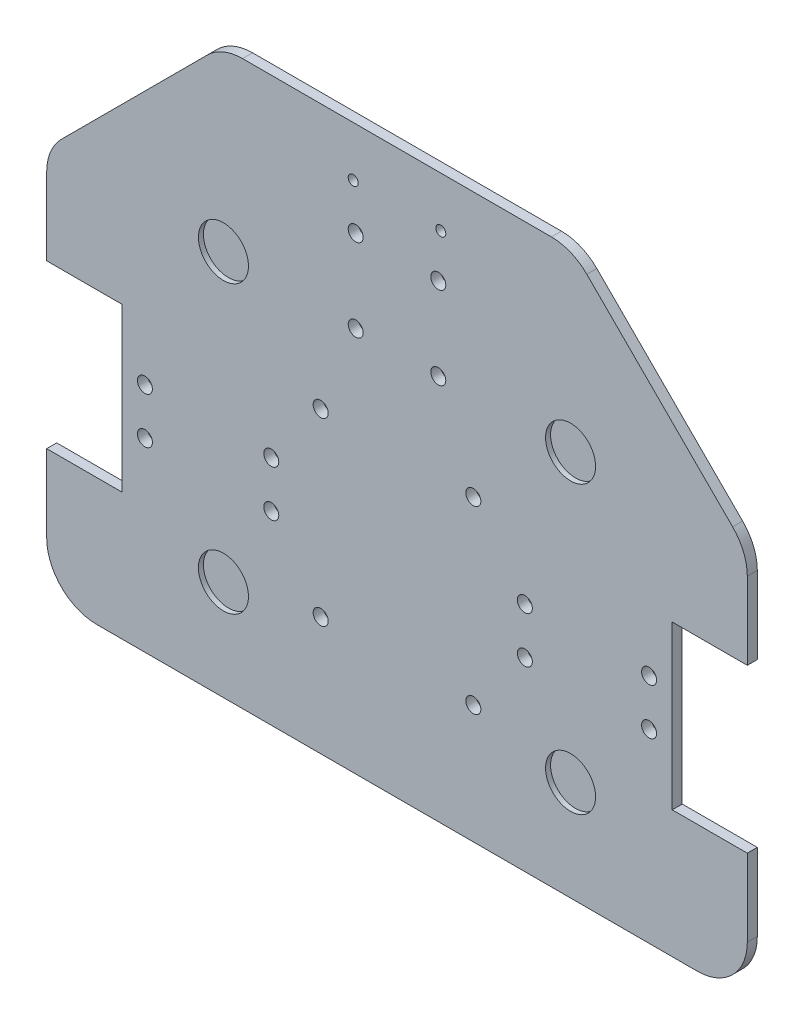
SolidWorks part; units mm, degrees
ref_plane "前视基准面" through (0, 0, 0) normal (0, 0, 1) x (1, 0, 0)
ref_plane "上视基准面" through (0, 0, 0) normal (0, 1, 0) x (1, 0, 0)
ref_plane "右视基准面" through (0, 0, 0) normal (1, 0, 0) x (0, 0, -1)
sketch "草图3" plane through (0, 0, 0) normal (0, 0, 1) x (1, 0, 0)
  line L1 (73.5057, 259.0895) -> (196.9372, 259.0895)
  line L2 (-4.7785, 180.8052) -> (-4.7785, 54.0895)
  line L3 (15.2215, 34.0895) -> (255.2215, 34.0895)
  line L4 (275.2215, 180.8052) -> (275.2215, 54.0895)
  line L6 (1.0793, 194.9474) -> (59.3636, 253.2316)
  line L9 (211.0793, 253.2316) -> (269.3636, 194.9474)
  arc A0 (73.5057, 259.0895) -> (59.3636, 253.2316) centre (73.5057, 239.0895) ccw
  arc A1 (211.0793, 253.2316) -> (196.9372, 259.0895) centre (196.9372, 239.0895) ccw
  arc A2 (1.0793, 194.9474) -> (-4.7785, 180.8052) centre (15.2215, 180.8052) ccw
  arc A3 (-4.7785, 54.0895) -> (15.2215, 34.0895) centre (15.2215, 54.0895) ccw
  arc A4 (255.2215, 34.0895) -> (275.2215, 54.0895) centre (255.2215, 54.0895) ccw
  arc A5 (275.2215, 180.8052) -> (269.3636, 194.9474) centre (255.2215, 180.8052) ccw
  dimension "D1" = 20
  dimension "D2" = 20
  dimension "D3" = 20
extrude "凸台-拉伸1" add sketch "草图3" along normal blind 4
sketch "电池槽" plane through (0, 0, 0) normal (0, 0, 1) x (1, 0, 0)
  line L0 (135.2215, 259.0895) -> (135.2215, 34.0895) construction
  line L1 (-4.7785, 117.4474) -> (275.2215, 117.4474) construction
  line L2 (99.7215, 158.4474) -> (99.7215, 76.4474)
  line L3 (99.7215, 76.4474) -> (170.7215, 76.4474)
  line L4 (170.7215, 158.4474) -> (170.7215, 76.4474)
  line L5 (107.7215, 150.4474) -> (162.7215, 150.4474)
  line L6 (59.3636, 253.2316) -> (1.0793, 194.9474)
  line L7 (-4.7785, 180.8052) -> (-4.7785, 54.0895)
  line L8 (15.2215, 34.0895) -> (255.2215, 34.0895)
  line L9 (275.2215, 54.0895) -> (275.2215, 180.8052)
  line L10 (269.3636, 194.9474) -> (211.0793, 253.2316)
  line L11 (196.9372, 259.0895) -> (73.5057, 259.0895)
  line L12 (59.3636, 253.2316) -> (1.0793, 194.9474)
  line L13 (-4.7785, 180.8052) -> (-4.7785, 54.0895)
  line L14 (15.2215, 34.0895) -> (255.2215, 34.0895)
  line L15 (275.2215, 54.0895) -> (275.2215, 180.8052)
  line L16 (269.3636, 194.9474) -> (211.0793, 253.2316)
  line L17 (196.9372, 259.0895) -> (73.5057, 259.0895)
  line L18 (107.7215, 150.4474) -> (107.7215, 84.4474)
  line L19 (107.7215, 84.4474) -> (162.7215, 84.4474)
  line L20 (162.7215, 150.4474) -> (162.7215, 84.4474)
  line L21 (107.7215, 150.4474) -> (162.7215, 84.4474) construction
  line L22 (107.7215, 84.4474) -> (162.7215, 150.4474) construction
  line L23 (99.7215, 158.4474) -> (170.7215, 158.4474)
  line L24 (99.7215, 158.4474) -> (107.7215, 150.4474) construction
  line L25 (107.7215, 84.4474) -> (99.7215, 76.4474) construction
  line L26 (162.7215, 84.4474) -> (170.7215, 76.4474) construction
  line L27 (162.7215, 150.4474) -> (170.7215, 158.4474) construction
  circle A4 centre (104.7215, 153.4474) radius 3
  circle A5 centre (104.7215, 81.4474) radius 3
  arc A6 (73.5057, 259.0895) -> (59.3636, 253.2316) centre (73.5057, 239.0895) ccw
  arc A7 (1.0793, 194.9474) -> (-4.7785, 180.8052) centre (15.2215, 180.8052) ccw
  arc A8 (-4.7785, 54.0895) -> (15.2215, 34.0895) centre (15.2215, 54.0895) ccw
  arc A9 (255.2215, 34.0895) -> (275.2215, 54.0895) centre (255.2215, 54.0895) ccw
  arc A10 (275.2215, 180.8052) -> (269.3636, 194.9474) centre (255.2215, 180.8052) ccw
  arc A11 (211.0793, 253.2316) -> (196.9372, 259.0895) centre (196.9372, 239.0895) ccw
  arc A12 (73.5057, 259.0895) -> (59.3636, 253.2316) centre (73.5057, 239.0895) ccw
  arc A13 (1.0793, 194.9474) -> (-4.7785, 180.8052) centre (15.2215, 180.8052) ccw
  arc A14 (-4.7785, 54.0895) -> (15.2215, 34.0895) centre (15.2215, 54.0895) ccw
  arc A15 (255.2215, 34.0895) -> (275.2215, 54.0895) centre (255.2215, 54.0895) ccw
  arc A16 (275.2215, 180.8052) -> (269.3636, 194.9474) centre (255.2215, 180.8052) ccw
  arc A17 (211.0793, 253.2316) -> (196.9372, 259.0895) centre (196.9372, 239.0895) ccw
  circle A18 centre (165.7215, 81.4474) radius 3
  circle A19 centre (165.7215, 153.4474) radius 3
  point P31 (135.2215, 117.4474)
  dimension "D2" = 8
  dimension "D1" = 0
sketch "轮槽" plane through (0, 0, 4) normal (0, 0, 1) x (1, 0, 0)
  line L4 (245.2215, 84.9474) -> (275.2215, 84.9474)
  line L5 (-4.7785, 149.9474) -> (7.2215, 149.9474)
  line L6 (59.3636, 253.2316) -> (1.0793, 194.9474)
  line L7 (-4.7785, 180.8052) -> (-4.7785, 54.0895)
  line L8 (15.2215, 34.0895) -> (255.2215, 34.0895)
  line L9 (275.2215, 54.0895) -> (275.2215, 180.8052)
  line L10 (269.3636, 194.9474) -> (211.0793, 253.2316)
  line L11 (196.9372, 259.0895) -> (73.5057, 259.0895)
  line L12 (59.3636, 253.2316) -> (1.0793, 194.9474)
  line L13 (-4.7785, 180.8052) -> (-4.7785, 54.0895)
  line L14 (15.2215, 34.0895) -> (255.2215, 34.0895)
  line L15 (275.2215, 54.0895) -> (275.2215, 180.8052)
  line L16 (269.3636, 194.9474) -> (211.0793, 253.2316)
  line L17 (196.9372, 259.0895) -> (73.5057, 259.0895)
  line L18 (7.2215, 149.9474) -> (25.2215, 149.9474)
  line L19 (25.2215, 149.9474) -> (25.2215, 84.9474)
  line L20 (25.2215, 84.9474) -> (-4.7785, 84.9474)
  line L21 (245.2215, 149.9474) -> (245.2215, 84.9474)
  line L22 (275.2215, 149.9474) -> (263.2215, 149.9474)
  line L23 (263.2215, 149.9474) -> (245.2215, 149.9474)
  arc A6 (73.5057, 259.0895) -> (59.3636, 253.2316) centre (73.5057, 239.0895) ccw
  arc A7 (1.0793, 194.9474) -> (-4.7785, 180.8052) centre (15.2215, 180.8052) ccw
  arc A8 (-4.7785, 54.0895) -> (15.2215, 34.0895) centre (15.2215, 54.0895) ccw
  arc A9 (255.2215, 34.0895) -> (275.2215, 54.0895) centre (255.2215, 54.0895) ccw
  arc A10 (275.2215, 180.8052) -> (269.3636, 194.9474) centre (255.2215, 180.8052) ccw
  arc A11 (211.0793, 253.2316) -> (196.9372, 259.0895) centre (196.9372, 239.0895) ccw
  arc A12 (73.5057, 259.0895) -> (59.3636, 253.2316) centre (73.5057, 239.0895) ccw
  arc A13 (1.0793, 194.9474) -> (-4.7785, 180.8052) centre (15.2215, 180.8052) ccw
  arc A14 (-4.7785, 54.0895) -> (15.2215, 34.0895) centre (15.2215, 54.0895) ccw
  arc A15 (255.2215, 34.0895) -> (275.2215, 54.0895) centre (255.2215, 54.0895) ccw
  arc A16 (275.2215, 180.8052) -> (269.3636, 194.9474) centre (255.2215, 180.8052) ccw
  arc A17 (211.0793, 253.2316) -> (196.9372, 259.0895) centre (196.9372, 239.0895) ccw
  point P0 (0, 0)
  line M18 (-4.7785, 180.8052) -> (-4.7785, 54.0895)
  line M22 (275.2215, 54.0895) -> (275.2215, 180.8052)
  dimension "D1" = 0
sketch "电机" plane through (0, 0, 0) normal (0, 0, 1) x (1, 0, 0)
  line L0 (25.2215, 117.4474) -> (25.2215, 135.9474) construction
  line L1 (25.2215, 149.9474) -> (25.2215, 84.9474) construction
  line L2 (25.2215, 117.4474) -> (25.2215, 98.9474) construction
  line L3 (25.2215, 135.9474) -> (32.2215, 135.9474) construction
  line L4 (32.2215, 135.9474) -> (56.2215, 135.9474) construction
  line L5 (56.2215, 135.9474) -> (78.2215, 135.9474) construction
  line L6 (78.2215, 135.9474) -> (94.2215, 135.9474) construction
  line L7 (94.2215, 135.9474) -> (94.2215, 98.9474) construction
  line L8 (94.2215, 98.9474) -> (25.2215, 98.9474) construction
  line L10 (25.2215, 135.9474) -> (94.2215, 135.9474)
  line L11 (177.0668, 98.9474) -> (245.2215, 98.9474) construction
  line L12 (177.0668, 135.9474) -> (177.0668, 98.9474) construction
  line L13 (192.2215, 135.9474) -> (177.0668, 135.9474) construction
  line L14 (214.2215, 135.9474) -> (192.2215, 135.9474) construction
  line L15 (238.2215, 135.9474) -> (214.2215, 135.9474) construction
  line L16 (245.2215, 135.9474) -> (238.2215, 135.9474) construction
  line L17 (245.2215, 117.4474) -> (245.2215, 98.9474) construction
  line L18 (245.2215, 117.4474) -> (245.2215, 135.9474) construction
  line L19 (94.2215, 135.9474) -> (94.2215, 98.9474)
  line L20 (94.2215, 98.9474) -> (25.2215, 98.9474)
  line L21 (25.2215, 98.9474) -> (25.2215, 135.9474)
  line L22 (177.0668, 135.9474) -> (245.2215, 135.9474)
  line L23 (245.2215, 135.9474) -> (245.2215, 98.9474)
  line L24 (245.2215, 98.9474) -> (177.0668, 98.9474)
  line L25 (177.0668, 98.9474) -> (177.0668, 135.9474)
  line L26 (56.2215, 135.9474) -> (56.2215, 117.4474) construction
  line L27 (-4.7785, 117.4474) -> (275.2215, 117.4474) construction
  line L28 (56.2215, 117.4474) -> (56.2215, 98.9474) construction
  line L29 (94.2215, 108.1974) -> (84.9715, 108.1974) construction
  line L30 (59.7215, 98.9474) -> (59.7215, 135.9474) construction
  circle A0 centre (84.9715, 108.1974) radius 3
  circle A1 centre (84.9715, 126.6974) radius 3
  circle A2 centre (34.4715, 108.1974) radius 3
  circle A3 centre (34.4715, 126.6974) radius 3
  circle A4 centre (186.3168, 126.6974) radius 3
  circle A5 centre (186.3168, 108.1974) radius 3
  circle A6 centre (235.9715, 108.1974) radius 3
  circle A7 centre (235.9715, 126.6974) radius 3
sketch "L298N" plane through (0, 0, 0) normal (0, 0, 1) x (1, 0, 0)
  line L0 (135.2215, 259.0895) -> (135.2215, 150.4474) construction
  line L1 (196.9372, 259.0895) -> (73.5057, 259.0895) construction
  line L2 (107.7215, 150.4474) -> (162.7215, 150.4474) construction
  line L4 (113.7215, 226.2684) -> (156.7215, 226.2684)
  line L5 (113.7215, 226.2684) -> (113.7215, 183.2684)
  line L6 (113.7215, 183.2684) -> (156.7215, 183.2684)
  line L7 (156.7215, 226.2684) -> (156.7215, 183.2684)
  line L8 (113.7215, 226.2684) -> (156.7215, 183.2684) construction
  line L9 (113.7215, 183.2684) -> (156.7215, 226.2684) construction
  circle A0 centre (118.7215, 188.2684) radius 3
  circle A2 centre (118.7215, 221.2684) radius 3
  circle A3 centre (151.7215, 221.2684) radius 3
  circle A4 centre (151.7215, 188.2684) radius 3
  point P6 (135.2215, 204.7684)
  point P28 (135.2215, 204.7684)
  dimension "D1" = 4
extrude "切除-拉伸3" cut sketch "电机" along normal blind 10 contours A7 | A4 | A0 | A6 | A5 | A1 | A3 | A2
extrude "切除-拉伸5" cut sketch "L298N" along normal blind 10 contours A0 | A2 | A4 | A3
extrude "切除-拉伸7" cut sketch "电池槽" along normal blind 10
extrude "切除-拉伸8" cut sketch "轮槽" against normal blind 10 contours L20 L19 L18 L5 M18 | L22 L23 L21 L4 M22
sketch "万向轮" plane through (0, 0, 0) normal (0, 0, 1) x (1, 0, 0)
  line L0 (135.2215, 259.0895) -> (135.2215, 219.0895) construction
  line L1 (196.9372, 259.0895) -> (73.5057, 259.0895) construction
  line L2 (158.7215, 239.0895) -> (111.7215, 239.0895) construction
  line L3 (152.7215, 239.0895) -> (117.7215, 239.0895)
  line L4 (111.7215, 239.0895) -> (125.647, 250.6363)
  line L5 (158.7215, 239.0895) -> (144.796, 250.6363)
  line L6 (158.7215, 239.0895) -> (144.796, 227.5426)
  line L7 (111.7215, 239.0895) -> (125.647, 227.5426)
  circle A0 centre (117.7215, 239.0895) radius 2
  circle A1 centre (152.7215, 239.0895) radius 2
  circle A2 centre (135.2215, 239.0895) radius 13.5
  circle A3 centre (135.2215, 239.0895) radius 15
  point P7 (135.2215, 239.0895)
  point P10 (135.2215, 239.0895)
extrude "切除-拉伸10" cut sketch "万向轮" along normal blind 10
ref_plane "基准面1" through (0, 0, 4) normal (0, 0, 1) x (1, 0, 0)
sketch "草图11" plane through (0, 0, 4) normal (0, 0, 1) x (1, 0, 0)
  line L0 (-3.2561, 188.4589) -> (273.6991, 188.4589) construction
  line L1 (65.8521, 257.5671) -> (65.8521, 34.0895) construction
  line L2 (15.2215, 34.0895) -> (255.2215, 34.0895) construction
  line L3 (204.5909, 257.5671) -> (204.5909, 34.0895) construction
  line L4 (-4.7785, 54.0895) -> (275.2215, 54.0895) construction
  arc A0 (1.0793, 194.9474) -> (-4.7785, 180.8052) centre (15.2215, 180.8052) ccw construction
  arc A1 (275.2215, 180.8052) -> (269.3636, 194.9474) centre (255.2215, 180.8052) ccw construction
  arc A2 (73.5057, 259.0895) -> (59.3636, 253.2316) centre (73.5057, 239.0895) ccw construction
  arc A3 (211.0793, 253.2316) -> (196.9372, 259.0895) centre (196.9372, 239.0895) ccw construction
  arc A4 (-4.7785, 54.0895) -> (15.2215, 34.0895) centre (15.2215, 54.0895) ccw construction
  circle A5 centre (65.8521, 188.4589) radius 10
  circle A6 centre (204.5909, 188.4589) radius 10
  circle A7 centre (65.8521, 74.0895) radius 10
  circle A8 centre (204.5909, 74.0895) radius 10
extrude "切除-拉伸11" cut sketch "草图11" against normal blind 2 contours A5 | A6 | A7 | A8
